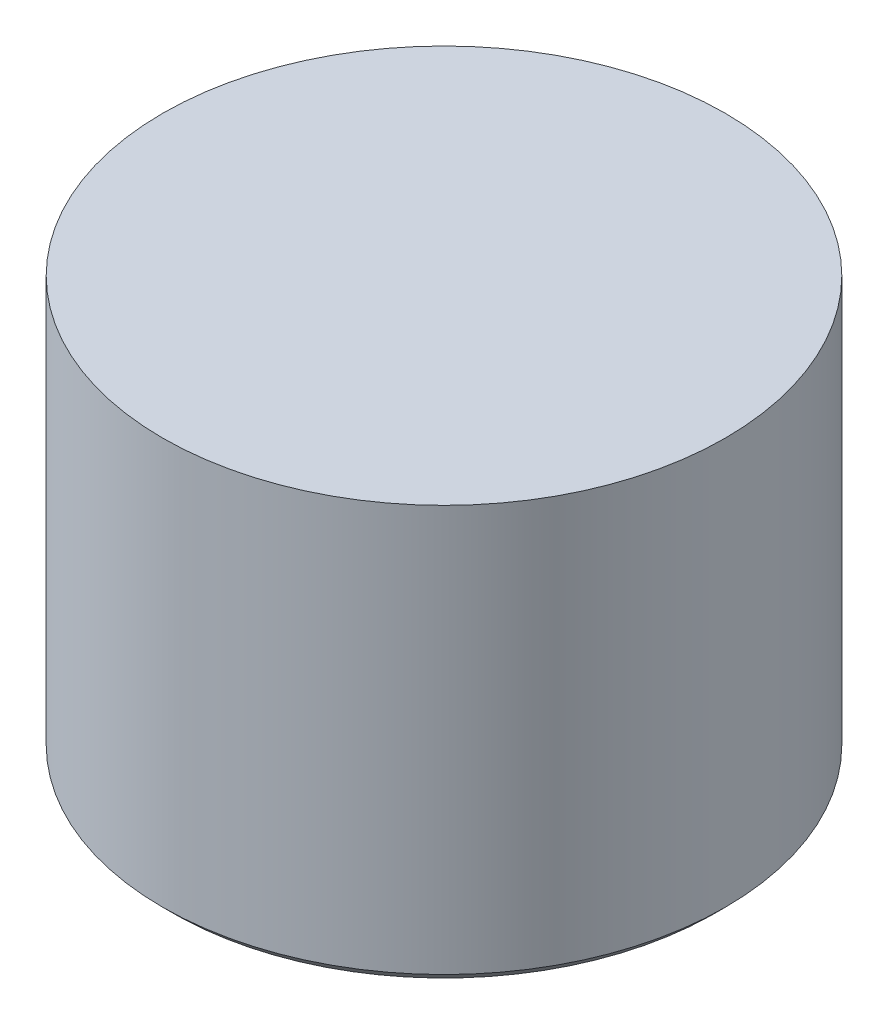
SolidWorks part; units mm, degrees
ref_plane "Front Plane" through (0, 0, 0) normal (0, 0, 1) x (1, 0, 0)
ref_plane "Top Plane" through (0, 0, 0) normal (0, 1, 0) x (1, 0, 0)
ref_plane "Right Plane" through (0, 0, 0) normal (1, 0, 0) x (0, 0, -1)
sketch "Sketch2" plane through (0, 0, 0) normal (0, 0, 1) x (1, 0, 0)
  line L0 (0, 0) -> (0, 38.0861) construction
  line L1 (0, 20) -> (0, 18)
  line L2 (0, 18) -> (1.5, 18)
  line L3 (1.5, 18) -> (1.5, 13)
  line L4 (1.5, 13) -> (3, 13)
  line L5 (3, 13) -> (3, 15)
  line L6 (6, 18) -> (9.5, 18)
  line L7 (12.5, 15) -> (12.5, 0)
  line L8 (12.5, 0) -> (13, 0)
  line L9 (13.5, 0.5) -> (13.5, 20)
  line L10 (13.5, 20) -> (0, 20)
  line L11 (9.5, 18) -> (12.5, 15)
  line L12 (3, 15) -> (6, 18)
  line L13 (13, 0) -> (13.5, 0.5)
  point P5 (3, 18)
  point P10 (12.5, 18)
  point P12 (13.5, 0)
  dimension "D1" = 2
  dimension "D2" = 1.5
  dimension "D3" = 3
  dimension "D4" = 5
  dimension "D5" = 20
  dimension "D6" = 2
  dimension "D7" = 1
  dimension "D8" = 12.5
revolve "Revolve1" add sketch "Sketch2" angle 360 about L0
